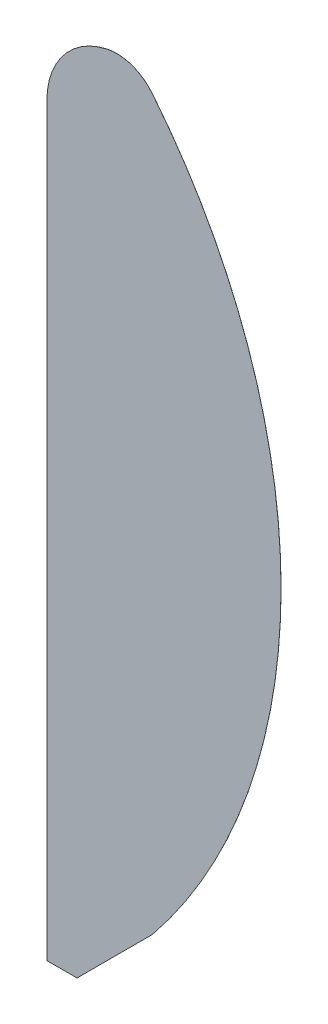
SolidWorks part; units mm, degrees
ref_plane "Front Plane" through (0, 0, 0) normal (1, 0, 0) x (0, 1, 0)
ref_plane "Top Plane" through (0, 0, 0) normal (0, 0, 1) x (0, 1, 0)
ref_plane "Right Plane" through (0, 0, 0) normal (0, 1, 0) x (-1, 0, 0)
sketch "Sketch1" plane through (0, 0, 0) normal (0, 0, 1) x (0, 1, 0)
  line L0 (0, 0) -> (0, 46433.2994) construction
  line L1 (0, 0) -> (-46433.2994, 0) construction
  line L2 (341.0561, 447.2498) -> (1519.4065, 281.6435) construction
  line L3 (0, 0) -> (123.624, 0)
  line L9 (0, 0) -> (0, -5)
  line L10 (0, -5) -> (12.5, -17.5)
  line L11 (0, 0) -> (72.9241, -38.8571)
  arc A0 (123.624, 0) -> (136, -10) centre (123.624, -12.6583) cw
  arc A1 (136, -10) -> (133.3481, -17.5) centre (128.5774, -11.5943) cw
  arc A2 (12.5, -17.5) -> (133.3481, -17.5) centre (72.9241, 57.298) ccw
  dimension "D1" = 123.624
  dimension "D2" = 5
  dimension "D3" = 38.8571
  dimension "D4" = 17.5
  dimension "Span" = 136
  dimension "D6" = 12.5
  dimension "D7" = 10
extrude "Boss-Extrude1" add sketch "Sketch1" along normal blind 0.01 contours L3 A0 A1 A2 L10 L9
equation "\"D3@Sketch1\"=\"Span@Sketch1\"/3.5"
equation "\"D1@Sketch1\"=\"Span@Sketch1\"*0.909"
